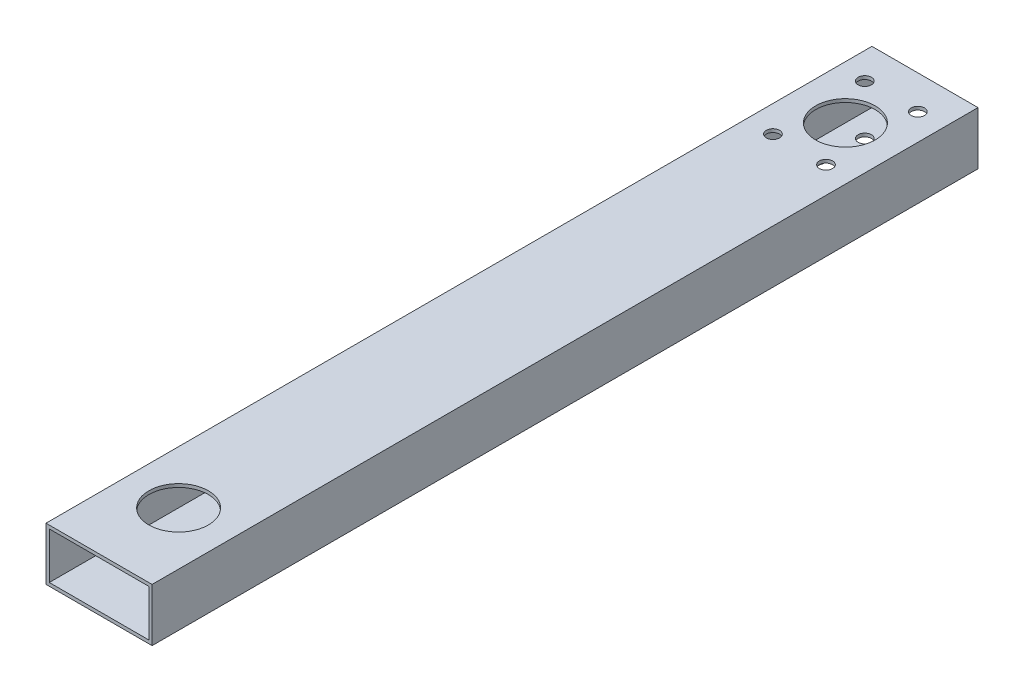
SolidWorks part; units mm, degrees
ref_plane "Front Plane" through (0, 0, 0) normal (0, 0, 1) x (1, 0, 0)
ref_plane "Top Plane" through (0, 0, 0) normal (0, 1, 0) x (1, 0, 0)
ref_plane "Right Plane" through (0, 0, 0) normal (1, 0, 0) x (0, 0, -1)
sketch "Sketch1" plane through (0, 0, 0) normal (0, 0, 1) x (1, 0, 0)
  line L0 (1.5875, 23.8125) -> (49.2125, 23.8125)
  line L1 (0, 0) -> (50.8, 0)
  line L2 (0, 0) -> (0, 25.4)
  line L3 (0, 25.4) -> (50.8, 25.4)
  line L4 (50.8, 0) -> (50.8, 25.4)
  line L5 (49.2125, 1.5875) -> (49.2125, 23.8125)
  line L6 (1.5875, 1.5875) -> (49.2125, 1.5875)
  line L7 (1.5875, 1.5875) -> (1.5875, 23.8125)
  dimension "D1" = 25.4
  dimension "D2" = 50.8
  dimension "D3" = 1.5875
extrude "Boss-Extrude1" add sketch "Sketch1" along normal blind 395.478
sketch "Sketch2" plane through (0, 25.4, 0) normal (0, 1, 0) x (1, 0, 0)
  line L0 (25.4, -38.1) -> (25.4, 0) construction
  line L1 (50.8, 0) -> (0, 0) construction
  line L2 (25.4, -395.478) -> (25.4, -357.378) construction
  line L3 (50.8, -395.478) -> (0, -395.478) construction
  circle A0 centre (25.4, -38.1) radius 14.224
  circle A1 centre (12.7, -16.103) radius 3.175
  circle A2 centre (12.7, -60.097) radius 3.175
  circle A3 centre (38.1, -60.097) radius 3.175
  circle A4 centre (38.1, -16.103) radius 3.175
  circle A5 centre (25.4, -357.378) radius 14.224
  point P16 (25.4, -395.478)
  dimension "D2" = 28.448
  dimension "D7" = 6.35
  dimension "D1" = 38.1
  dimension "D3" = 12.7
  dimension "D4" = 25.4
  dimension "D5" = 12.7
  dimension "D6" = 25.4
  dimension "D8" = 38.1
extrude "Cut-Extrude1" cut sketch "Sketch2" against normal through all both and the other way through all
